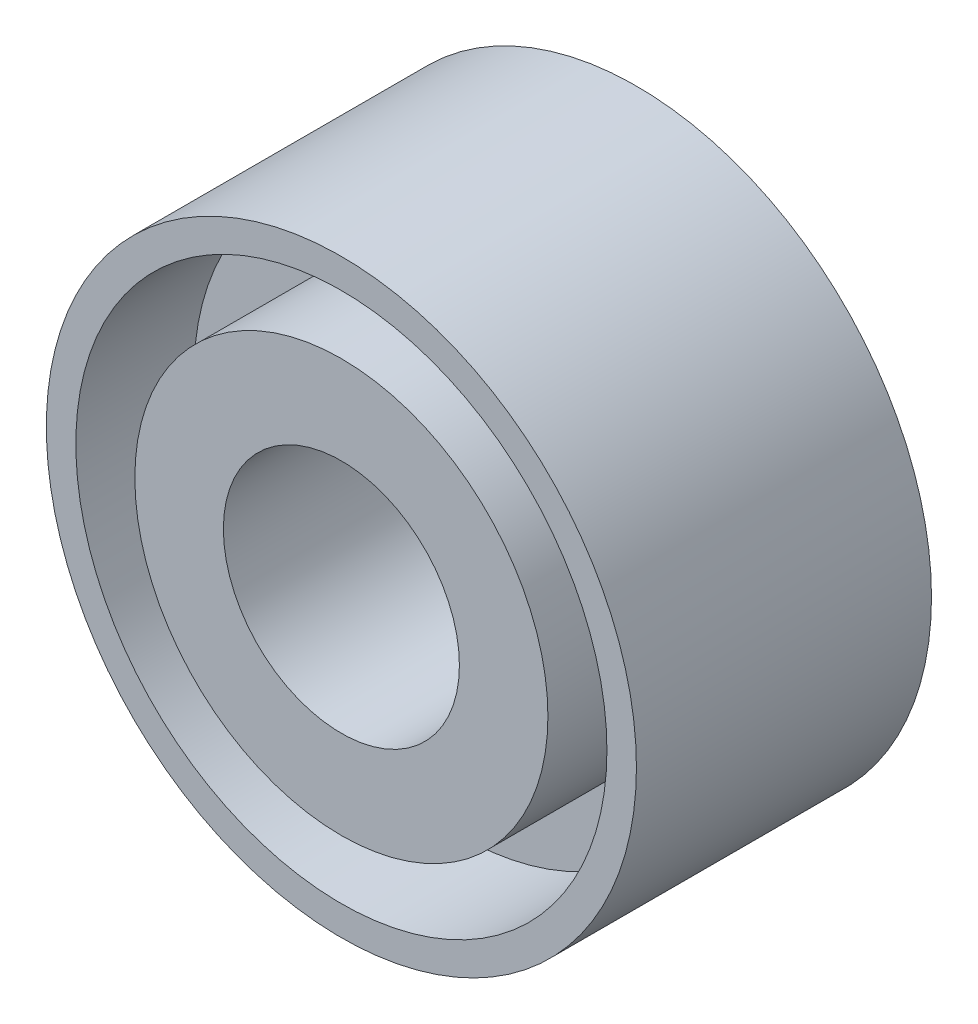
SolidWorks part; units mm, degrees
ref_plane "Front Plane" through (0, 0, 0) normal (0, 0, 1) x (1, 0, 0)
ref_plane "Top Plane" through (0, 0, 0) normal (0, 1, 0) x (1, 0, 0)
ref_plane "Right Plane" through (0, 0, 0) normal (1, 0, 0) x (0, 0, -1)
sketch "Sketch1" plane through (0, 0, 0) normal (0, 0, 1) x (1, 0, 0)
  circle A0 centre (0, 0) radius 2
  circle A1 centre (0, 0) radius 5
  dimension "D1" = 4
  dimension "D2" = 10
extrude "Boss-Extrude1" add sketch "Sketch1" along normal blind 5
sketch "Sketch2" plane through (0, 0, 5) normal (0, 0, 1) x (1, 0, 0)
  circle A2 centre (0, 0) radius 4.5
  circle A3 centre (0, 0) radius 3.5
  circle A4 centre (0, 0) radius 3.5
  dimension "D1" = 1.5
  dimension "D2" = 1
extrude "Cut-Extrude1" cut sketch "Sketch2" against normal blind 2 contours A2 | A4
